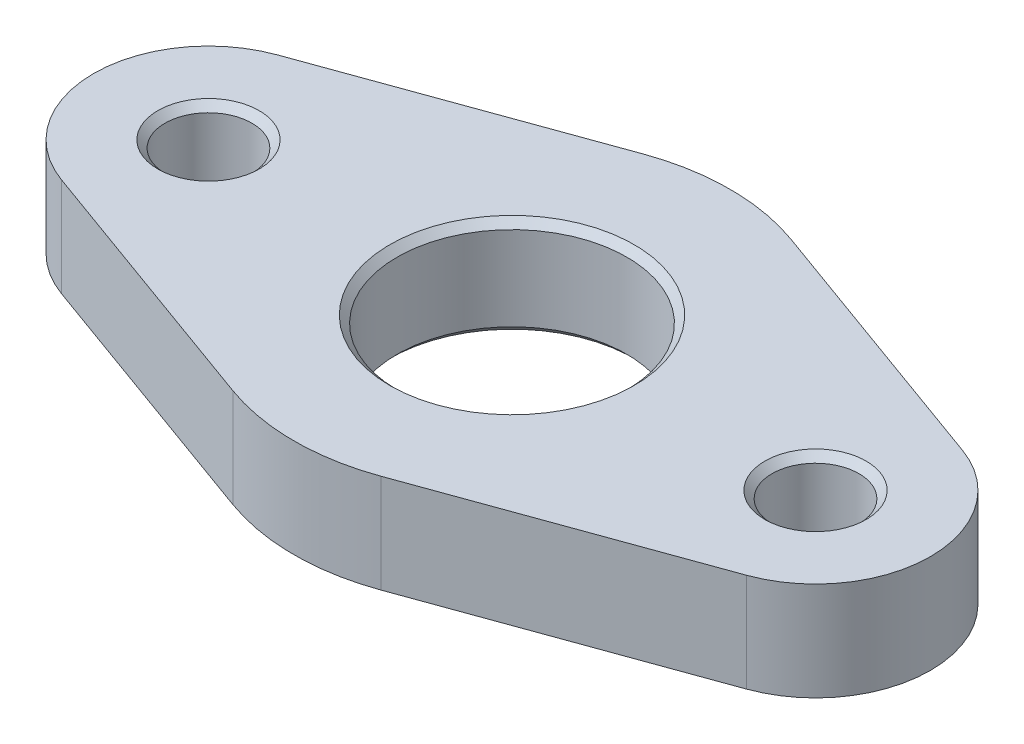
SolidWorks part; units mm, degrees
ref_plane "Front Plane" through (0, 0, 0) normal (0, 0, 1) x (1, 0, 0)
ref_plane "Top Plane" through (0, 0, 0) normal (0, 1, 0) x (1, 0, 0)
ref_plane "Right Plane" through (0, 0, 0) normal (1, 0, 0) x (0, 0, -1)
sketch "Sketch1" plane through (0, 0, 0) normal (0, 1, 0) x (1, 0, 0)
  line L0 (-37.8654, 11.9444) -> (-8.189, 22.6661)
  line L1 (-8.9857, 0) -> (11.0126, 0) construction
  line L2 (0, -12.3638) -> (0, 9.3911) construction
  line L3 (-37.8654, -11.9444) -> (-8.189, -22.6661)
  line L4 (37.8654, -11.9444) -> (8.189, -22.6661)
  line L5 (37.8654, 11.9444) -> (8.189, 22.6661)
  arc A0 (-8.189, -22.6661) -> (8.189, -22.6661) centre (0, 0) ccw
  arc A1 (-37.8654, 11.9444) -> (-37.8654, -11.9444) centre (-33.55, 0) ccw
  arc A2 (37.8654, 11.9444) -> (37.8654, -11.9444) centre (33.55, 0) cw
  arc A3 (8.189, 22.6661) -> (-8.189, 22.6661) centre (0, 0) ccw
  point P11 (0, 0)
  dimension "D1" = 48.2
  dimension "D2" = 25.4
  dimension "D3" = 33.55
extrude "Boss-Extrude1" add sketch "Sketch1" along normal blind 10.9
sketch "Sketch3" plane through (0, 10.9, 0) normal (0, 1, 0) x (1, 0, 0)
  line L0 (0, 7.2503) -> (0, -8.0731) construction
  circle A0 centre (0, 0) radius 12.7
  circle A1 centre (-33.55, 0) radius 4.8
  circle A2 centre (33.55, 0) radius 4.8
  dimension "D1" = 25.4
  dimension "D2" = 9.6
extrude "Cut-Extrude1" cut sketch "Sketch3" against normal blind 10.9
chamfer "Chamfer1" distance 0.8 angle 45 3 edges at (33.55, 10.9, -4.8) (0, 10.9, 12.7) (-33.55, 10.9, 4.8)
chamfer "Chamfer2" distance 0.8 angle 45 3 edges at (33.55, 0, -4.8) (0, 0, 12.7) (-33.55, 0, 4.8)
